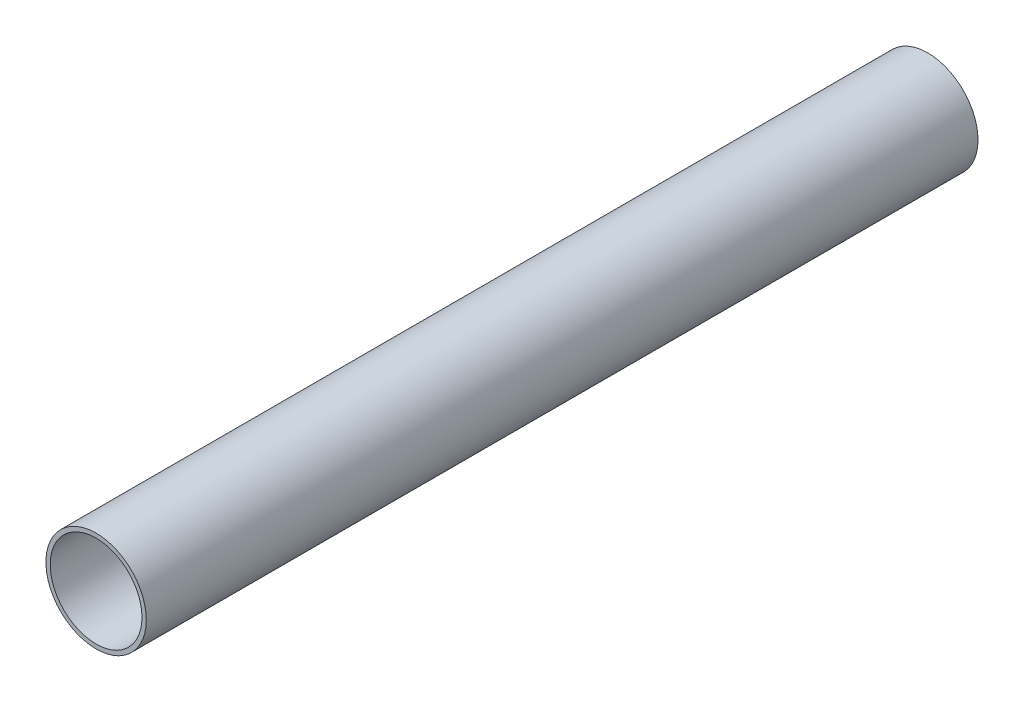
SolidWorks part; units mm, degrees
ref_plane "정면" through (0, 0, 0) normal (0, 0, 1) x (1, 0, 0)
ref_plane "윗면" through (0, 0, 0) normal (0, 1, 0) x (1, 0, 0)
ref_plane "우측면" through (0, 0, 0) normal (1, 0, 0) x (0, 0, -1)
sketch "스케치1" plane through (0, 0, 0) normal (0, 0, 1) x (1, 0, 0)
  circle A0 centre (0, 0) radius 17.5
  circle A1 centre (0, 0) radius 16
  dimension "D1" = 32
  dimension "D2" = 35
extrude "보스-돌출1" add sketch "스케치1" along normal blind 290
